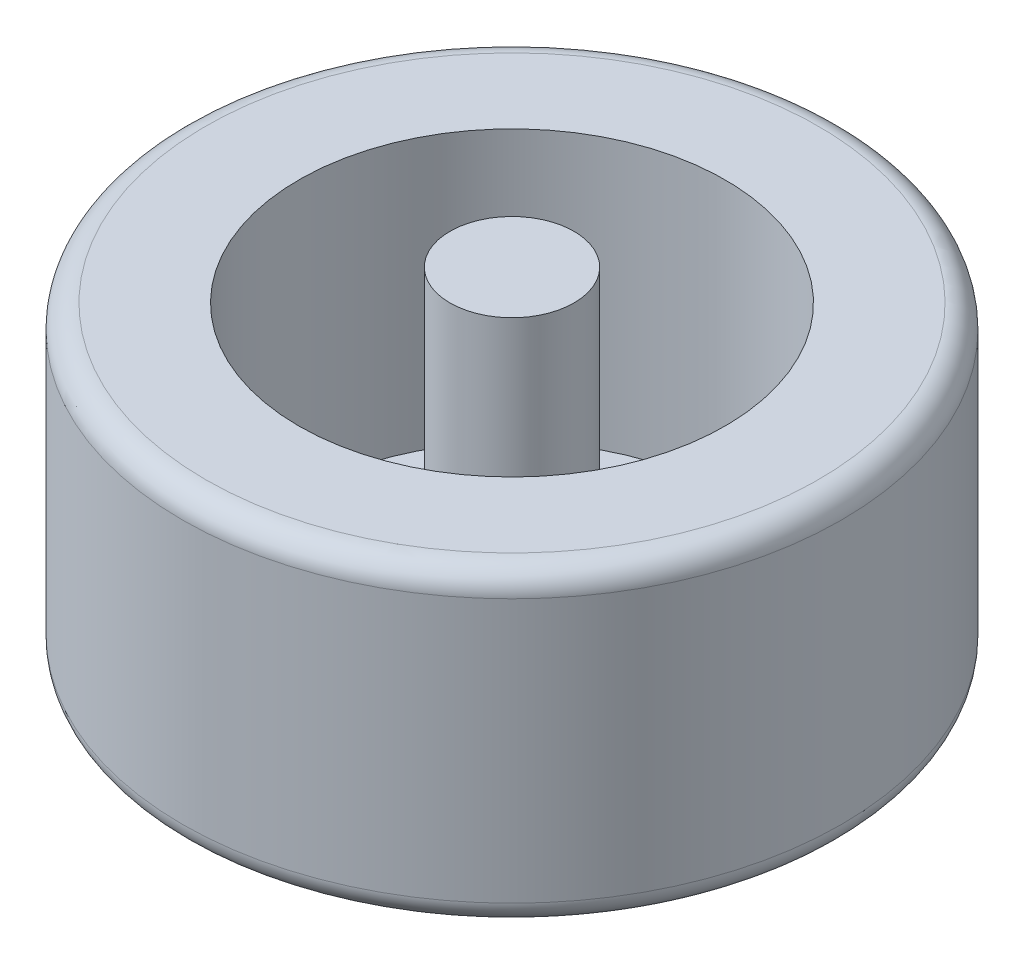
SolidWorks part; units mm, degrees
ref_plane "Спереди" through (0, 0, 0) normal (0, 0, 1) x (1, 0, 0)
ref_plane "Сверху" through (0, 0, 0) normal (0, 1, 0) x (1, 0, 0)
ref_plane "Справа" through (0, 0, 0) normal (1, 0, 0) x (0, 0, -1)
other "Configuration Table"
sketch "Эскиз1" plane through (0, 0, 0) normal (0, 1, 0) x (1, 0, 0)
  circle A1 centre (0, 0) radius 42.5
extrude "Бобышка-Вытянуть1" add sketch "Эскиз1" along normal blind 40
sketch "Эскиз2" plane through (0, 40, 0) normal (0, 1, 0) x (1, 0, 0)
  circle A0 centre (0, 0) radius 27.5
  circle A1 centre (0, 0) radius 8
extrude "Вырез-Вытянуть1" cut sketch "Эскиз2" against normal blind 35
sketch "Эскиз3" plane through (0, 5, 0) normal (0, 1, 0) x (1, 0, 0)
  line L0 (0, 27.5) -> (0, 8) construction
  circle A2 centre (0, 0) radius 27.5 construction
  circle A3 centre (0, 0) radius 27.5 construction
  circle A4 centre (0, 0) radius 8 construction
  circle A5 centre (0, 17.75) radius 4
extrude "Вырез-Вытянуть2" cut sketch "Эскиз3" against normal blind 35
pattern_circular "Круговой массив1" count 8 over 360 about axis through (0, 0, 0) along (0, 1, 0) of "Вырез-Вытянуть2"
sketch "Эскиз4" plane through (0, 0, 0) normal (0, -1, 0) x (1, 0, 0)
  circle A0 centre (0, 0) radius 27.5
extrude "Вырез-Вытянуть3" cut sketch "Эскиз4" against normal blind 2
sketch "Эскиз5" plane through (0, 40, 0) normal (0, 1, 0) x (1, 0, 0)
  circle A0 centre (0, 0) radius 8
extrude "Бобышка-Вытянуть2" add sketch "Эскиз5" along normal blind 4
fillet "Скругление1" radius 3 2 edges at (0, 0, 42.5) (0, 40, 42.5)
